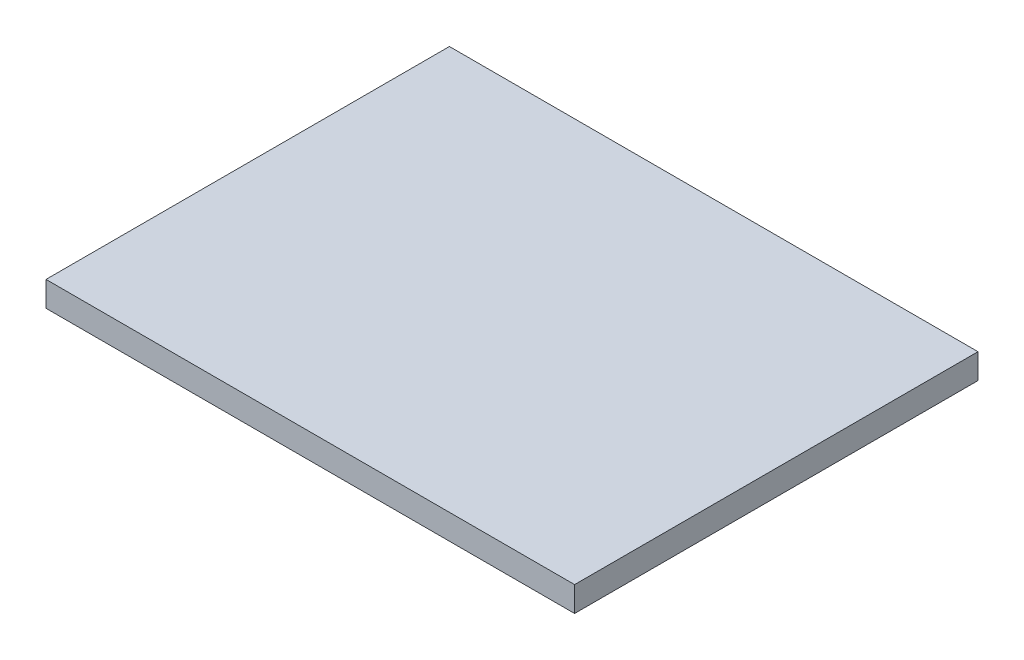
SolidWorks part; units mm, degrees
ref_plane "Front Plane" through (0, 0, 0) normal (0, 0, 1) x (1, 0, 0)
ref_plane "Top Plane" through (0, 0, 0) normal (0, 1, 0) x (1, 0, 0)
ref_plane "Right Plane" through (0, 0, 0) normal (1, 0, 0) x (0, 0, -1)
sketch "Sketch1" plane through (0, 0, 0) normal (0, 1, 0) x (1, 0, 0)
  line L1 (-190, -145) -> (190, -145)
  line L2 (-190, -145) -> (-190, 145)
  line L3 (-190, 145) -> (190, 145)
  line L4 (190, -145) -> (190, 145)
  line L5 (-190, -145) -> (190, 145) construction
  line L6 (-190, 145) -> (190, -145) construction
  point P0 (0, 0)
  dimension "D1" = 380
  dimension "D2" = 290
extrude "Boss-Extrude1" add sketch "Sketch1" along normal blind 18
equation "\"Case_Width\" = 790mm"
equation "\"Case_Depth\" = 470mm"
equation "\"Tank_Width\" = 660mm"
equation "\"WoodSheet_Thickness\" = 18mm"
equation "\"D1@Boss-Extrude1\"=\"WoodSheet_Thickness\""
